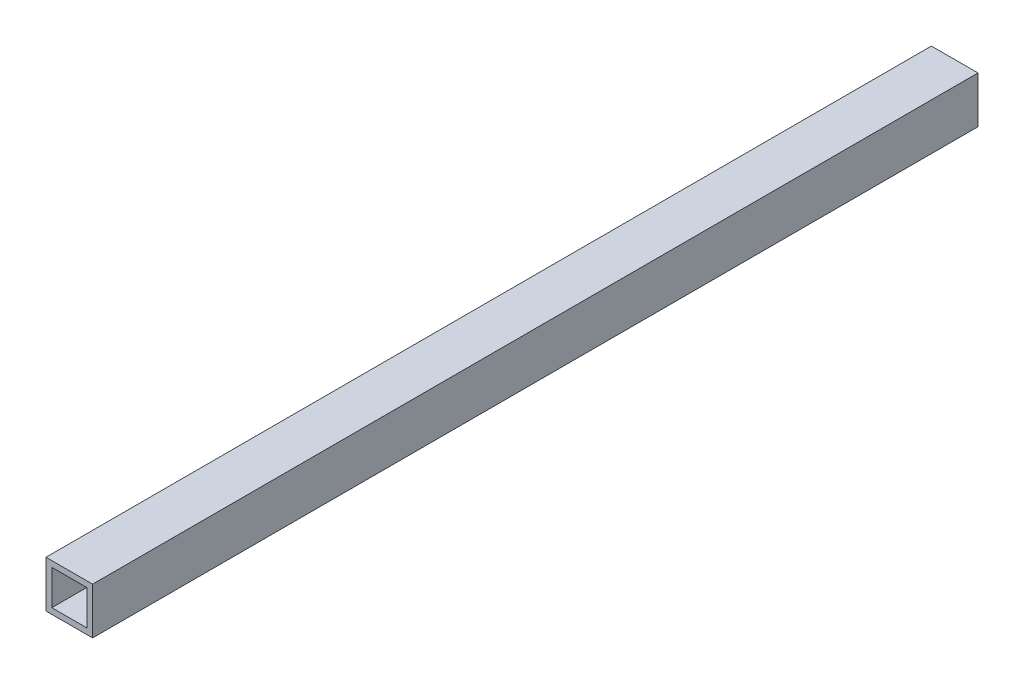
SolidWorks part; units mm, degrees
ref_plane "Front Plane" through (0, 0, 0) normal (0, 0, 1) x (1, 0, 0)
ref_plane "Top Plane" through (0, 0, 0) normal (0, 1, 0) x (1, 0, 0)
ref_plane "Right Plane" through (0, 0, 0) normal (1, 0, 0) x (0, 0, -1)
sketch "Sketch1" plane through (0, 0, 0) normal (0, 0, 1) x (1, 0, 0)
  line L1 (0, 0) -> (25.4, 0)
  line L2 (0, 0) -> (0, 25.4)
  line L3 (0, 25.4) -> (25.4, 25.4)
  line L4 (25.4, 0) -> (25.4, 25.4)
  line L5 (3.175, 22.225) -> (22.225, 22.225)
  line L6 (3.175, 22.225) -> (3.175, 3.175)
  line L7 (3.175, 3.175) -> (22.225, 3.175)
  line L8 (22.225, 22.225) -> (22.225, 3.175)
  dimension "D1" = 25.4
  dimension "D2" = 25.4
  dimension "D3" = 3.175
  dimension "D4" = 3.175
  dimension "D5" = 3.175
extrude "Boss-Extrude1" add sketch "Sketch1" along normal blind 482.6
